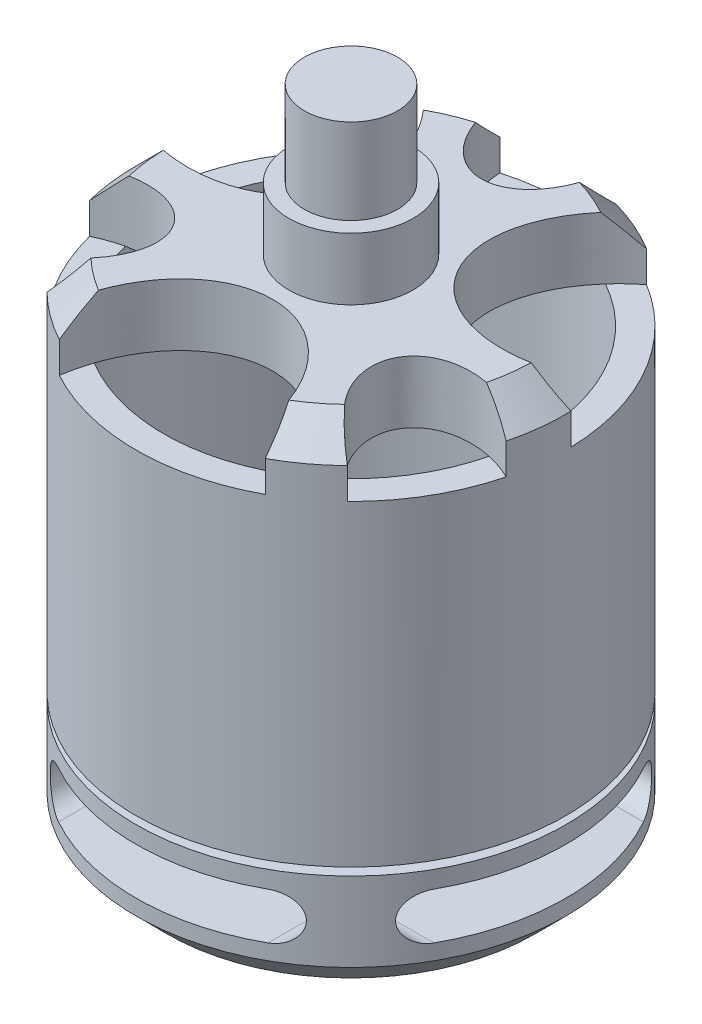
SolidWorks part; units mm, degrees
ref_plane "Front Plane" through (0, 0, 0) normal (0, 0, 1) x (1, 0, 0)
ref_plane "Top Plane" through (0, 0, 0) normal (0, 1, 0) x (1, 0, 0)
ref_plane "Right Plane" through (0, 0, 0) normal (1, 0, 0) x (0, 0, -1)
sketch "Sketch1" plane through (0, 0, 0) normal (0, 0, 1) x (1, 0, 0)
  line L0 (-3.2, 0) -> (-13.85, 0)
  line L1 (55, 0) -> (-55, 0) construction
  line L2 (-13.85, 0) -> (-13.85, 7.1)
  line L3 (-13.85, 32) -> (-4, 32)
  line L4 (-4, 32) -> (-4, 36)
  line L5 (-4, 36) -> (-3, 36)
  line L6 (-3, 36) -> (-3, 41.5)
  line L11 (0, 41.5) -> (0, -2.5)
  line L12 (-3, 41.5) -> (0, 41.5)
  line L13 (-3.2, 0) -> (-3.2, -2.5)
  line L14 (-3.2, -2.5) -> (0, -2.5)
  line L15 (0, -55) -> (0, 55) construction
  line L16 (-13.85, 7.6) -> (-13.85, 32)
  line L17 (-13.85, 7.6) -> (-12.85, 7.6)
  line L19 (-13.85, 7.1) -> (-12.85, 7.1)
  line L20 (-12.85, 7.6) -> (-12.85, 7.1)
  dimension "D1" = 13.85
  dimension "D2" = 32
  dimension "D3" = 9.5
  dimension "D4" = 3
  dimension "D5" = 2.5
  dimension "D6" = 3.2
  dimension "D7" = 4
  dimension "D8" = 1
  dimension "D9" = 0.5
  dimension "D10" = 1
  dimension "D11" = 7.1
revolve "Revolve1" add sketch "Sketch1" angle 360 about L11
chamfer "Chamfer1" distance 2 angle 45 2 edges at (-13.85, 0, 0) (-13.85, 32, 0)
sketch "Sketch2" plane through (0, 32, 0) normal (0, 1, 0) x (1, 0, 0)
  line L0 (0, -15.235) -> (0, 15.235) construction
  line L1 (59.3167, 205.15) -> (351.9833, 205.15) construction
  ellipse E0 centre (0, -13.85) end of major axis (0, -5.0348) minor radius 6.763
  ellipse E1 centre (0, 13.85) end of major axis (0, 8.4033) minor radius 3.7629
  ellipse E2 centre (-77.9574, 6.3737) end of major axis (-77.9574, 15.1889) minor radius 6.763
  ellipse E3 centre (-77.9574, 34.0737) end of major axis (-77.9574, 39.5204) minor radius 3.7629
extrude "Cut-Extrude1" cut sketch "Sketch2" against normal blind 4
pattern_circular "CirPattern1" count 3 over 360 about axis through (0, 41.5, 0) along (0, 1, 0) of "Cut-Extrude1"
sketch "Sketch3" plane through (0, 28, 0) normal (0, 1, 0) x (1, 0, 0)
  line L0 (59.3167, 205.15) -> (351.9833, 205.15) construction
  circle A0 centre (0, 0) radius 12.055
extrude "Cut-Extrude2" cut sketch "Sketch3" against normal blind 20
sketch "Sketch4" plane through (0, 0, 0) normal (1, 0, 0) x (0, 0, -1)
  line L0 (-6.75, 4.5) -> (6.75, 4.5) construction
  line L1 (-6.75, 6) -> (6.75, 6)
  line L2 (-6.75, 3) -> (6.75, 3)
  line L3 (0, 15.235) -> (0, -15.235) construction
  line L4 (13.85, 2) -> (-13.85, 2) construction
  arc A0 (-6.75, 6) -> (-6.75, 3) centre (-6.75, 4.5) ccw
  arc A1 (6.75, 3) -> (6.75, 6) centre (6.75, 4.5) ccw
  point P2 (0, 4.5)
  dimension "D1" = 13.5
  dimension "D2" = 3
  dimension "D3" = 1
extrude "Cut-Extrude3" cut sketch "Sketch4" against normal through all both and the other way through all
pattern_circular "CirPattern3" count 2 over 90 about axis through (0, 41.5, 0) along (0, 1, 0) of "Cut-Extrude3"
sketch "Sketch5" plane through (0, 0, 0) normal (0, -1, 0) x (1, 0, 0)
  line L0 (15.235, 0) -> (-15.235, 0) construction
  line L1 (0, -15.235) -> (0, 15.235) construction
  circle A0 centre (-9.5, 0) radius 1.75
  circle A1 centre (0, 8) radius 1.75
  circle A2 centre (9.5, 0) radius 1.75
  circle A3 centre (0, -8) radius 1.75
  dimension "D1" = 3.5
  dimension "D2" = 16
  dimension "D3" = 19
  dimension "D4" = 9.5
  dimension "D5" = 8
extrude "Cut-Extrude4" cut sketch "Sketch5" against normal blind 1
